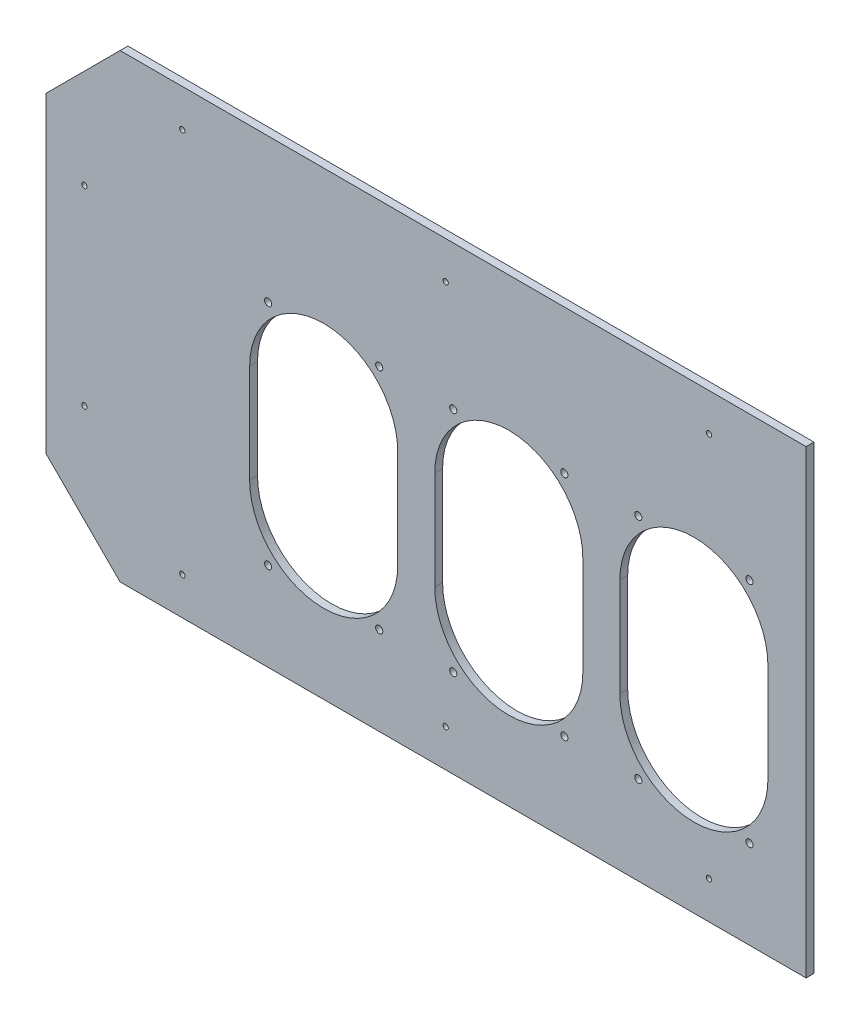
SolidWorks part; units mm, degrees
material "Pin"
ref_plane "Plan de face" through (0, 0, 0) normal (0, 0, 1) x (1, 0, 0)
ref_plane "Plan de dessus" through (0, 0, 0) normal (0, 1, 0) x (1, 0, 0)
ref_plane "Plan de droite" through (0, 0, 0) normal (1, 0, 0) x (0, 0, -1)
sketch "Esquisse1" plane through (0, 0, 0) normal (0, 0, 1) x (1, 0, 0)
  line L0 (-307.3, 186.475) -> (307.3, -186.475) construction
  line L1 (-307.3, 186.475) -> (307.3, 186.475)
  line L2 (-307.3, 186.475) -> (-307.3, -186.475)
  line L3 (-307.3, -186.475) -> (307.3, -186.475)
  line L4 (307.3, 186.475) -> (307.3, -186.475)
  line L5 (-307.3, -186.475) -> (307.3, 186.475) construction
  point P4 (0, 0)
  dimension "D1" = 372.95
  dimension "D2" = 614.6
extrude "Boss.-Extru.1" add sketch "Esquisse1" along normal mid plane 6.35
sketch "Esquisse2" plane through (0, 0, 3.175) normal (0, 0, 1) x (1, 0, 0)
  line L7 (-82.3, 17.475) -> (-82.3, -62.525) construction
  line L8 (-22.3, 17.475) -> (-22.3, -62.525)
  line L9 (-142.3, 17.475) -> (-142.3, -62.525)
  line L10 (-307.3, 186.475) -> (-307.3, -186.475) construction
  line L11 (-307.3, -186.475) -> (307.3, -186.475) construction
  arc A1 (-22.3, 17.475) -> (-142.3, 17.475) centre (-82.3, 17.475) ccw
  arc A2 (-142.3, -62.525) -> (-22.3, -62.525) centre (-82.3, -62.525) ccw
  point P2 (-82.3, -22.525)
  dimension "D1" = 225
  dimension "D2" = 60
  dimension "D3" = 80
  dimension "D4" = 123.95
extrude "Enlèv. mat.-Extru.1" cut sketch "Esquisse2" against normal through all
hole_wizard "Dégagement #121" positions "Esquisse7" profile "Esquisse8" hole size "#12" standard "Ansi Inch" end condition through all
sketch "Esquisse7" plane through (0, 0, 3.175) normal (0, 0, 1) x (1, 0, 0)
  line L0 (-142.3, 17.475) -> (-142.3, -62.525) construction
  arc A1 (-142.3, -62.525) -> (-22.3, -62.525) centre (-82.3, -62.525) ccw construction
  arc A2 (-22.3, 17.475) -> (-142.3, 17.475) centre (-82.3, 17.475) ccw construction
  point P0 (-127.3, -114.8318)
  point P2 (-37.3, -114.8318)
  point P4 (-37.3, 69.7818)
  point P6 (-127.3, 69.7818)
  dimension "D1" = 69
  dimension "D2" = 69
  dimension "D3" = 69
  dimension "D4" = 15
sketch "Esquisse8" plane through (-127.3, -114.8318, 3.175) normal (1, 0, 0) x (0, -1, 0)
  line L0 (0, 0) -> (0, 6.35)
  line L1 (0, 6.35) -> (2.8956, 6.35)
  line L2 (2.8956, 6.35) -> (2.8956, 0)
  line L5 (2.8956, 0) -> (0, 0)
  line L11 (0, -6.35) -> (0, 107.95) construction
  dimension "Diamètre du perçage jusqu'au prochain" = 5.7912
  dimension "Profondeur du perçage jusqu'au prochain" = 6.35
pattern_linear "Répétition linéaire1" count 3 spacing 150 along (1, 0, 0) of "Enlèv. mat.-Extru.1", "Dégagement #121"
sketch "Esquisse9" plane through (0, 0, -3.175) normal (0, 0, -1) x (-1, 0, 0)
  line L0 (247.302, 186.475) -> (307.3, 126.477)
  line L1 (-307.3, 186.475) -> (307.3, 186.475) construction
  line L2 (307.3, 186.475) -> (307.3, -186.475) construction
  line L3 (307.3, 126.477) -> (307.3, 186.475)
  line L4 (307.3, 186.475) -> (247.302, 186.475)
  dimension "D1" = 84.85
extrude "Enlèv. mat.-Extru.2" cut sketch "Esquisse9" against normal through all
sketch "Esquisse10" plane through (0, 0, 3.175) normal (0, 0, 1) x (1, 0, 0)
  line L0 (-307.3, -186.475) -> (307.3, -186.475) construction
  line L1 (307.3, 186.475) -> (308.65, 186.475)
  line L2 (307.3, 186.475) -> (307.3, -186.475)
  line L3 (307.3, -186.475) -> (308.65, -186.475)
  line L4 (308.65, 186.475) -> (308.65, -186.475)
  line L5 (307.3, 186.475) -> (308.65, -186.475) construction
  line L6 (307.3, -186.475) -> (308.65, 186.475) construction
  point P4 (307.975, 0)
  dimension "D1" = 1.35
extrude "Boss.-Extru.3" add sketch "Esquisse10" against normal through all
hole_wizard "Dégagement #61" positions "Esquisse13" profile "Esquisse14" hole size "#6" standard "Ansi Inch" end condition through all
sketch "Esquisse13" plane through (0, 0, -3.175) normal (0, 0, -1) x (-1, 0, 0)
  line L0 (0, 0) -> (-39.8433, 0) construction
  point P0 (276.225, -77.375)
  point P2 (196.85, -156.075)
  point P4 (-16.55, -156.075)
  point P6 (-229.95, -156.075)
  point P11 (-229.95, 156.075)
  point P12 (-16.55, 156.075)
  point P13 (196.85, 156.075)
  point P14 (276.225, 77.375)
  dimension "D1" = 156.075
  dimension "D2" = 229.95
  dimension "D3" = 156.075
  dimension "D4" = 16.55
  dimension "D5" = 196.85
  dimension "D6" = 156.075
  dimension "D7" = 276.225
  dimension "D8" = 77.375
sketch "Esquisse14" plane through (-276.225, -77.375, -3.175) normal (1, 0, 0) x (0, 1, 0)
  line L0 (0, 0) -> (0, 6.35)
  line L1 (0, 6.35) -> (2.1526, 6.35)
  line L2 (2.1526, 6.35) -> (2.1526, 0)
  line L5 (2.1526, 0) -> (0, 0)
  line L11 (0, -6.35) -> (0, 107.95) construction
  dimension "Diamètre du perçage jusqu'au prochain" = 4.3053
  dimension "Profondeur du perçage jusqu'au prochain" = 6.35
mirror "Symétrie1" about plane through (0, 0, 0) normal (0, 1, 0) of "Enlèv. mat.-Extru.2"
mirror "Symétrie2" [suppressed]
delete or keep bodies "Corps-Supprimer/Garder 1" [suppressed] type delete bodies bodies 114
